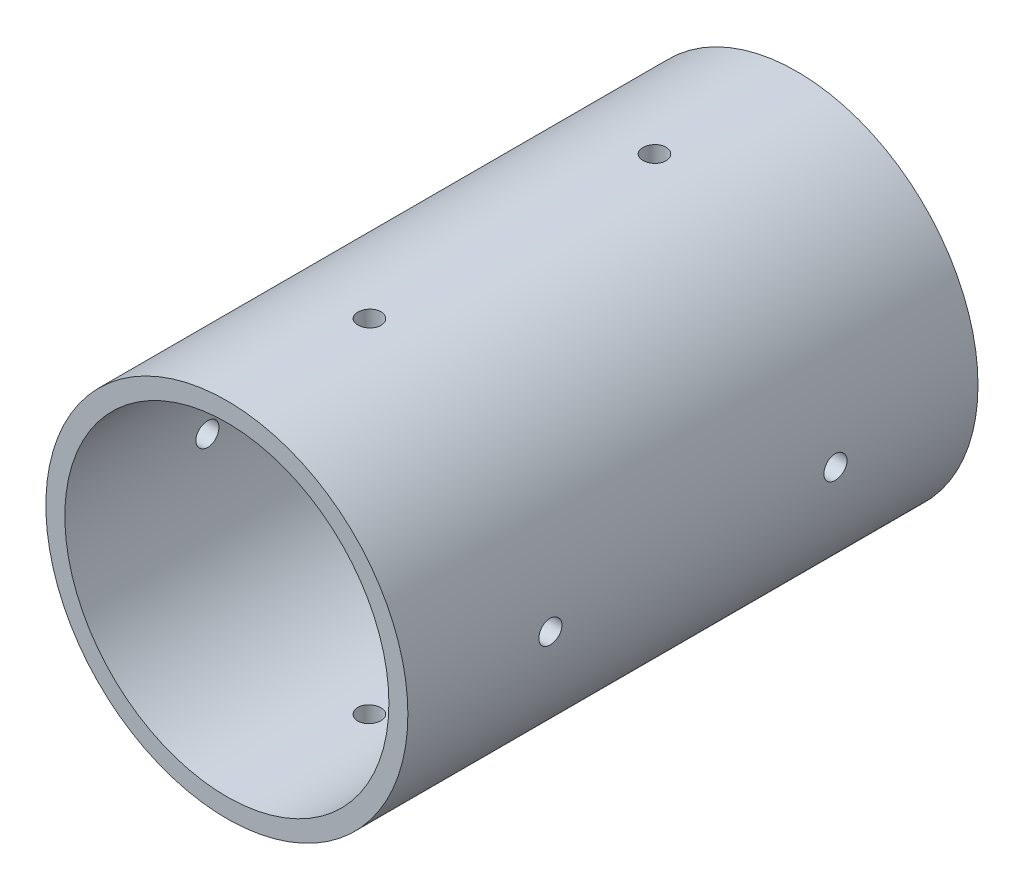
SolidWorks part; units mm, degrees
material "7075-T6 (SN)"
ref_plane "Front" through (0, 0, 0) normal (0, 0, 1) x (1, 0, 0)
ref_plane "Top" through (0, 0, 0) normal (0, 1, 0) x (1, 0, 0)
ref_plane "Right" through (0, 0, 0) normal (1, 0, 0) x (0, 0, -1)
sketch "Sketch1" plane through (0, 0, 0) normal (0, 0, 1) x (1, 0, 0)
  circle A0 centre (0, 0) radius 15.875
  circle A1 centre (0, 0) radius 14.2108
  dimension "D1" = 31.75
  dimension "D2" = 28.4216
extrude "Boss-Extrude1" add sketch "Sketch1" along normal blind 50
sketch "Sketch2" plane through (0, 0, 0) normal (0, 1, 0) x (1, 0, 0)
  line L0 (0, 0) -> (0, -50) construction
  line L1 (-15.875, -50) -> (15.875, -50) construction
  line L2 (14.2108, 0) -> (-14.2108, 0) construction
  line L3 (-15.875, -25) -> (15.875, -25) construction
  line L4 (-15.875, 0) -> (-15.875, -50) construction
  line L5 (15.875, -50) -> (15.875, 0) construction
  circle A0 centre (0, -12.5) radius 1.0125
  circle A1 centre (0, -312.5) radius 1.0125
  circle A2 centre (0, -37.5) radius 1.0125
  circle A3 centre (0, -62.5) radius 1.0125
  circle A4 centre (0, -87.5) radius 1.0125
  circle A5 centre (0, -112.5) radius 1.0125
  circle A6 centre (0, -137.5) radius 1.0125
  circle A7 centre (0, -162.5) radius 1.0125
  circle A8 centre (0, -187.5) radius 1.0125
  circle A9 centre (0, -212.5) radius 1.0125
  circle A10 centre (0, -237.5) radius 1.0125
  circle A11 centre (0, -262.5) radius 1.0125
  circle A12 centre (0, -287.5) radius 1.0125
  circle A13 centre (0, -337.5) radius 1.0125
  circle A20 centre (0, -312.5) radius 1.0125 [skipped]
  circle A21 centre (0, -337.5) radius 1.0125 [skipped]
  circle A22 centre (0, -362.5) radius 1.0125 [skipped]
  circle A23 centre (0, -387.5) radius 1.0125 [skipped]
  circle A24 centre (0, -412.5) radius 1.0125 [skipped]
  circle A25 centre (0, -437.5) radius 1.0125 [skipped]
  circle A26 centre (0, -462.5) radius 1.0125 [skipped]
  dimension "D1" = 2.025
  dimension "D2" = 12.5
  dimension "D3" = 2.025
  dimension "D4" = 25
  dimension "D7" = 25
  dimension "D6" = 25
  dimension "D5" = 18
extrude "Cut-Extrude1" cut sketch "Sketch2" against normal up to surface and the other way up to surface up to face at (15.875, 0, 50) other way up to face at (15.875, 0, 50)
sketch "Sketch3" plane through (0, 0, 0) normal (1, 0, 0) x (0, 0, -1)
  line L0 (0, 0) -> (-50, 0) construction
  line L1 (-50, 15.875) -> (-50, -15.875) construction
  line L2 (0, -14.2108) -> (0, 14.2108) construction
  circle A0 centre (-12.5, 0) radius 1.0125
  circle A2 centre (-37.5, 0) radius 1.0125
  circle A3 centre (-62.5, 0) radius 1.0125
  circle A4 centre (-87.5, 0) radius 1.0125
  circle A5 centre (-112.5, 0) radius 1.0125
  circle A6 centre (-137.5, 0) radius 1.0125
  circle A7 centre (-162.5, 0) radius 1.0125
  circle A8 centre (-187.5, 0) radius 1.0125
  circle A9 centre (-212.5, 0) radius 1.0125
  circle A10 centre (-237.5, 0) radius 1.0125
  circle A11 centre (-262.5, 0) radius 1.0125
  circle A12 centre (-287.5, 0) radius 1.0125
  circle A20 centre (-312.5, 0) radius 1.0125 [skipped]
  circle A21 centre (-337.5, 0) radius 1.0125 [skipped]
  circle A22 centre (-362.5, 0) radius 1.0125 [skipped]
  circle A23 centre (-387.5, 0) radius 1.0125 [skipped]
  circle A24 centre (-412.5, 0) radius 1.0125 [skipped]
  circle A25 centre (-437.5, 0) radius 1.0125 [skipped]
  circle A26 centre (-462.5, 0) radius 1.0125 [skipped]
  dimension "D2" = 2.025
  dimension "D3" = 12.5
  dimension "D5" = 2.025
  dimension "D6" = 25
  dimension "D7" = 18
extrude "Cut-Extrude2" cut sketch "Sketch3" against normal up to surface and the other way up to surface up to face at (0.2306, -15.8733, 36.5141) other way up to face at (0.2306, -15.8733, 36.5141)
